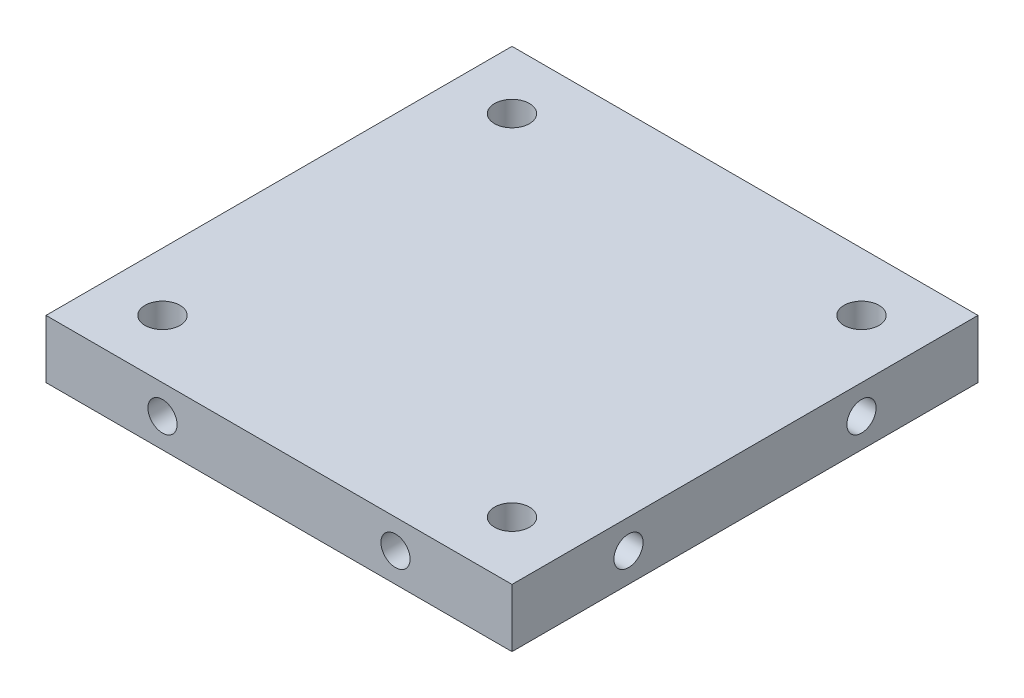
SolidWorks part; units mm, degrees
material "PET"
ref_plane "Front Plane" through (0, 0, 0) normal (0, 0, 1) x (1, 0, 0)
ref_plane "Top Plane" through (0, 0, 0) normal (0, 1, 0) x (1, 0, 0)
ref_plane "Right Plane" through (0, 0, 0) normal (1, 0, 0) x (0, 0, -1)
sketch "Sketch1" plane through (0, 0, 0) normal (0, 1, 0) x (1, 0, 0)
  line L1 (-20, -20) -> (20, -20)
  line L2 (-20, -20) -> (-20, 20)
  line L3 (-20, 20) -> (20, 20)
  line L4 (20, -20) -> (20, 20)
  line L5 (-20, -20) -> (20, 20) construction
  line L6 (-20, 20) -> (20, -20) construction
  point P0 (0, 0)
  dimension "D1" = 40
  dimension "D2" = 40
extrude "Boss-Extrude1" add sketch "Sketch1" along normal blind 5
sketch "Sketch2" plane through (0, 0, 20) normal (0, 0, 1) x (1, 0, 0)
  circle A0 centre (-10, 2.5) radius 1.25
  circle A1 centre (10, 2.5) radius 1.25
extrude "Cut-Extrude1" cut sketch "Sketch2" against normal blind 5
pattern_circular "CirPattern1" count 4 every 90 about axis through (0, 0, 0) along (0, 1, 0) of "Cut-Extrude1"
sketch "Sketch3" plane through (0, 5, 0) normal (0, 1, 0) x (1, 0, 0)
  line L5 (-15, -15) -> (15, 15) construction
  line L6 (-15, 15) -> (15, -15) construction
  circle A0 centre (-15, 15) radius 1.5
  circle A1 centre (15, 15) radius 1.5
  circle A2 centre (15, -15) radius 1.5
  circle A3 centre (-15, -15) radius 1.5
  point P0 (0, 0)
  dimension "D1" = 30
  dimension "D2" = 30
extrude "Cut-Extrude3" cut sketch "Sketch3" against normal blind 10
